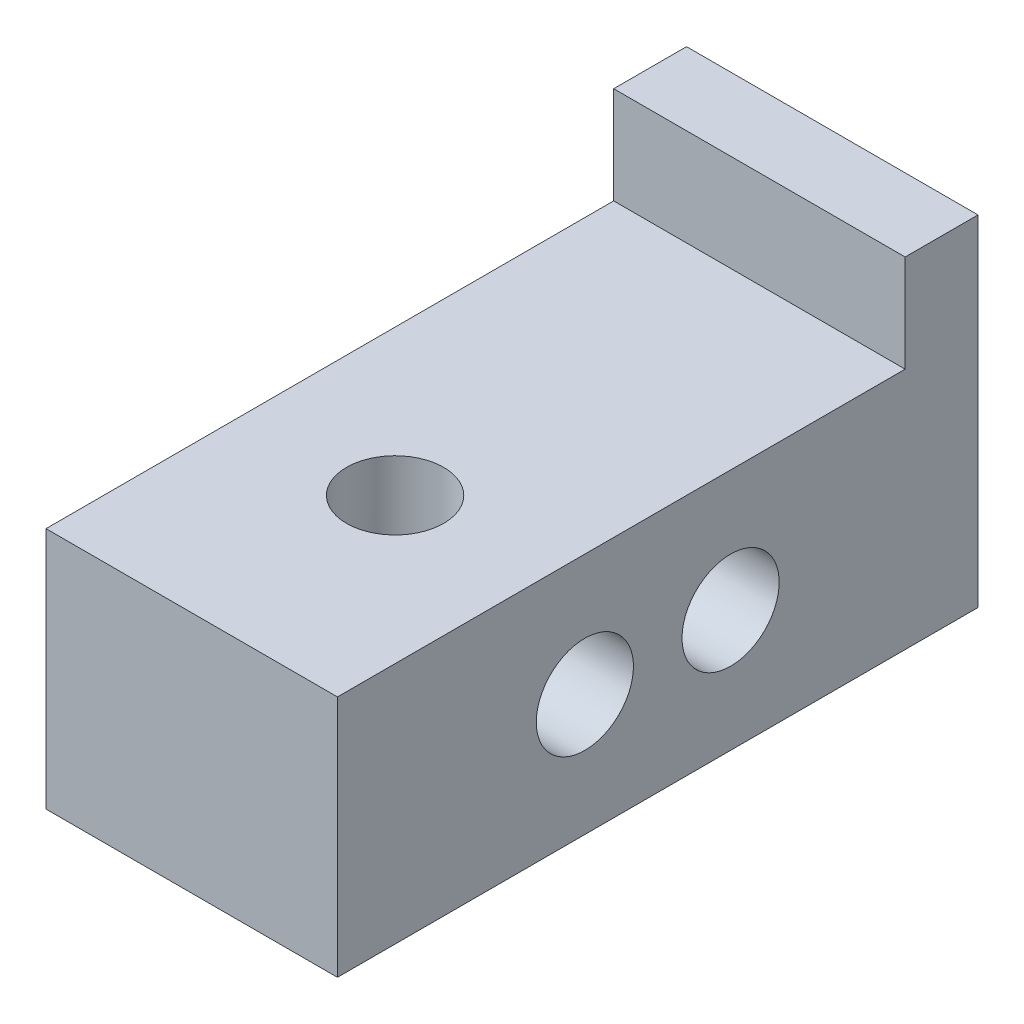
SolidWorks part; units mm, degrees
ref_plane "Front Plane" through (0, 0, 0) normal (0, 0, 1) x (1, 0, 0)
ref_plane "Top Plane" through (0, 0, 0) normal (0, 1, 0) x (1, 0, 0)
ref_plane "Right Plane" through (0, 0, 0) normal (1, 0, 0) x (0, 0, -1)
sketch "Sketch1" plane through (0, 0, 0) normal (0, 1, 0) x (1, 0, 0)
  line L0 (0, 0) -> (0, 15) construction
  line L1 (-6, 15) -> (6, 15)
  line L2 (-6, 15) -> (-6, -8.3734)
  line L3 (-6, -8.3734) -> (6, -8.3734)
  line L4 (6, -8.3734) -> (6, 15)
  circle A0 centre (0, 0) radius 2
  point P7 (0, 15)
  dimension "D1" = 4
  dimension "D2" = 15
  dimension "D3" = 12
extrude "Boss-Extrude1" add sketch "Sketch1" along normal blind 10
sketch "Sketch2" plane through (0, 10, 0) normal (0, 1, 0) x (1, 0, 0)
  line L0 (6, -8.3734) -> (6, 15) construction
  line L1 (-6, 15) -> (6, 15)
  line L2 (-6, 15) -> (-6, 18)
  line L3 (-6, 18) -> (6, 18)
  line L4 (6, 15) -> (6, 18)
  line L5 (0, 18) -> (0, 15) construction
  line L6 (-6, 16.5) -> (6, 16.5) construction
  point P404 (0, 16.5)
  dimension "D1" = 3
extrude "Boss-Extrude2" add sketch "Sketch2" against normal blind 10 and the other way blind 4
sketch "Sketch3" plane through (-6, 0, 0) normal (-1, 0, 0) x (0, 0, 1)
  line L0 (-7.8133, 5) -> (-1.8133, 5) construction
  line L1 (-4.8133, 5) -> (-4.8133, 0) construction
  line L2 (-18, 0) -> (8.3734, 0) construction
  circle A0 centre (-7.8133, 5) radius 2
  circle A1 centre (-1.8133, 5) radius 2
  dimension "D1" = 4
  dimension "D2" = 4
  dimension "D3" = 6
  dimension "D4" = 5
extrude "Cut-Extrude1" cut sketch "Sketch3" against normal blind 14
